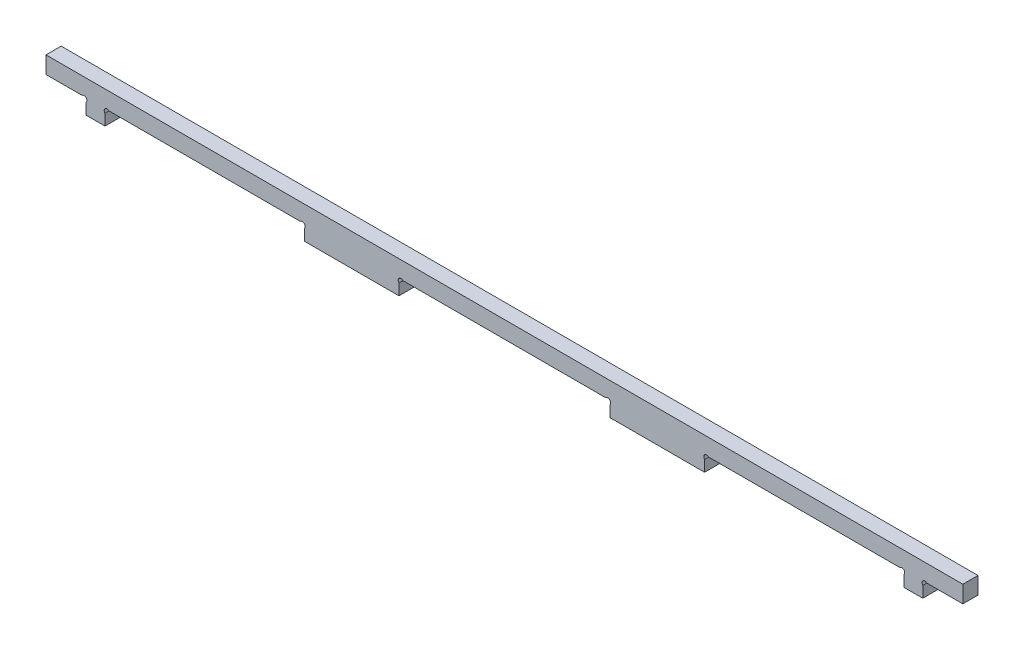
SolidWorks part; units mm, degrees
ref_plane "Plan de face" through (0, 0, 0) normal (0, 0, 1) x (1, 0, 0)
ref_plane "Plan de dessus" through (0, 0, 0) normal (0, 1, 0) x (1, 0, 0)
ref_plane "Plan de droite" through (0, 0, 0) normal (1, 0, 0) x (0, 0, -1)
sketch "Esquisse1" plane through (0, 0, 0) normal (0, 0, 1) x (1, 0, 0)
  line L136 (65.7875, 76.5822) -> (111.5449, 76.5822)
  line L137 (113.6662, 74.4609) -> (113.6662, 70.7035)
  line L138 (111.5449, 68.5822) -> (65.7875, 68.5822)
  line L139 (63.6662, 70.7035) -> (63.6662, 74.4609)
  line L140 (-47.6662, 70.7035) -> (-47.6662, 74.4609)
  line L141 (-95.5449, 68.5822) -> (-49.7875, 68.5822)
  line L142 (-97.6662, 74.4609) -> (-97.6662, 70.7035)
  line L143 (-49.7875, 76.5822) -> (-95.5449, 76.5822)
  line L144 (-212.8507, 74.4609) -> (-212.8507, 70.7035)
  line L145 (220.9721, 76.5822) -> (226.7294, 76.5822)
  line L146 (218.8507, 74.4609) -> (218.8507, 70.7035)
  line L147 (220.9721, 68.5822) -> (226.7294, 68.5822)
  line L148 (228.8507, 74.4609) -> (228.8507, 70.7035)
  line L149 (-204.9721, 68.5822) -> (-210.7294, 68.5822)
  line L150 (-202.8507, 74.4609) -> (-202.8507, 70.7035)
  line L151 (-204.9721, 76.5822) -> (-210.7294, 76.5822)
  arc A71 (63.6662, 70.7035) -> (65.7875, 68.5822) centre (64.7269, 69.6429) ccw
  arc A72 (65.7875, 76.5822) -> (63.6662, 74.4609) centre (64.7269, 75.5216) ccw
  arc A73 (113.6662, 74.4609) -> (111.5449, 76.5822) centre (112.6055, 75.5216) ccw
  arc A74 (111.5449, 68.5822) -> (113.6662, 70.7035) centre (112.6055, 69.6429) ccw
  arc A75 (-95.5449, 68.5822) -> (-97.6662, 70.7035) centre (-96.6055, 69.6429) cw
  arc A76 (-97.6662, 74.4609) -> (-95.5449, 76.5822) centre (-96.6055, 75.5216) cw
  arc A77 (-49.7875, 76.5822) -> (-47.6662, 74.4609) centre (-48.7269, 75.5216) cw
  arc A78 (-47.6662, 70.7035) -> (-49.7875, 68.5822) centre (-48.7269, 69.6429) cw
  arc A79 (220.9721, 76.5822) -> (218.8507, 74.4609) centre (219.9114, 75.5216) ccw
  arc A80 (228.8507, 74.4609) -> (226.7294, 76.5822) centre (227.7901, 75.5216) ccw
  arc A81 (226.7294, 68.5822) -> (228.8507, 70.7035) centre (227.7901, 69.6429) ccw
  arc A82 (218.8507, 70.7035) -> (220.9721, 68.5822) centre (219.9114, 69.6429) ccw
  arc A83 (-202.8507, 70.7035) -> (-204.9721, 68.5822) centre (-203.9114, 69.6429) cw
  arc A84 (-210.7294, 68.5822) -> (-212.8507, 70.7035) centre (-211.7901, 69.6429) cw
  arc A85 (-212.8507, 74.4609) -> (-210.7294, 76.5822) centre (-211.7901, 75.5216) cw
  arc A86 (-204.9721, 76.5822) -> (-202.8507, 74.4609) centre (-203.9114, 75.5216) cw
sketch "Esquisse2" plane through (0, 0, 0) normal (0, 0, 1) x (1, 0, 0)
  line L0 (-95.5449, 68.5822) -> (-49.7875, 68.5822) construction
  line L1 (-234, 77.5822) -> (250, 77.5822)
  line L2 (-234, 77.5822) -> (-234, 68.5822)
  line L3 (-234, 68.5822) -> (-214.9721, 68.5822)
  line L4 (250, 77.5822) -> (250, 68.5822)
  line L6 (-212.8507, 72.5822) -> (228.8507, 72.5822) construction
  line L7 (-212.8507, 74.4609) -> (-212.8507, 70.7035) construction
  line L8 (228.8507, 74.4609) -> (228.8507, 70.7035) construction
  line L9 (8, 72.5822) -> (8, 121.922) construction
  line L10 (8, 72.5822) -> (8, 68.5822) construction
  line L11 (-212.8507, 66.4609) -> (-212.8507, 60.5822)
  line L12 (-212.8507, 60.5822) -> (-202.8507, 60.5822)
  line L13 (-202.8507, 60.5822) -> (-202.8507, 66.4609)
  line L14 (-200.7294, 68.5822) -> (-99.7875, 68.5822)
  line L15 (-212.8507, 72.5822) -> (-212.8507, 68.5822) construction
  line L16 (-202.8507, 72.5822) -> (-202.8507, 68.5822) construction
  line L17 (-97.6662, 72.5822) -> (-97.6662, 68.5822) construction
  line L18 (-97.6662, 74.4609) -> (-97.6662, 70.7035) construction
  line L19 (-47.6662, 72.5822) -> (-47.6662, 68.5822) construction
  line L20 (-47.6662, 70.7035) -> (-47.6662, 74.4609) construction
  line L21 (63.6662, 72.5822) -> (63.6662, 68.5822) construction
  line L22 (63.6662, 70.7035) -> (63.6662, 74.4609) construction
  line L23 (113.6662, 72.5822) -> (113.6662, 68.5822) construction
  line L24 (113.6662, 74.4609) -> (113.6662, 70.7035) construction
  line L25 (228.8507, 72.5822) -> (228.8507, 68.5822) construction
  line L26 (218.8507, 72.5822) -> (218.8507, 68.5822) construction
  line L27 (218.8507, 74.4609) -> (218.8507, 70.7035) construction
  line L28 (228.8507, 66.4609) -> (228.8507, 60.5822)
  line L29 (228.8507, 60.5822) -> (218.8507, 60.5822)
  line L30 (218.8507, 60.5822) -> (218.8507, 66.4609)
  line L31 (113.6662, 66.4609) -> (113.6662, 60.5822)
  line L32 (113.6662, 60.5822) -> (63.6662, 60.5822)
  line L33 (63.6662, 60.5822) -> (63.6662, 66.4609)
  line L34 (-97.6662, 66.4609) -> (-97.6662, 60.5822)
  line L35 (-97.6662, 60.5822) -> (-47.6662, 60.5822)
  line L36 (-47.6662, 60.5822) -> (-47.6662, 66.4609)
  line L37 (-45.5449, 68.5822) -> (61.5449, 68.5822)
  line L38 (115.7875, 68.5822) -> (216.7294, 68.5822)
  line L39 (230.9721, 68.5822) -> (250, 68.5822)
  arc A0 (-212.8507, 70.7035) -> (-210.7294, 68.5822) centre (-211.7901, 69.6429) ccw construction
  arc A1 (-204.9721, 68.5822) -> (-202.8507, 70.7035) centre (-203.9114, 69.6429) ccw construction
  arc A2 (-97.6662, 70.7035) -> (-95.5449, 68.5822) centre (-96.6055, 69.6429) ccw construction
  arc A3 (-49.7875, 68.5822) -> (-47.6662, 70.7035) centre (-48.7269, 69.6429) ccw construction
  arc A4 (111.5449, 68.5822) -> (113.6662, 70.7035) centre (112.6055, 69.6429) ccw construction
  arc A5 (226.7294, 68.5822) -> (228.8507, 70.7035) centre (227.7901, 69.6429) ccw construction
  arc A6 (218.8507, 70.7035) -> (220.9721, 68.5822) centre (219.9114, 69.6429) ccw construction
  arc A7 (-212.8507, 66.4609) -> (-214.9721, 68.5822) centre (-213.9114, 67.5216) ccw
  arc A8 (-200.7294, 68.5822) -> (-202.8507, 66.4609) centre (-201.7901, 67.5216) ccw
  arc A9 (-97.6662, 66.4609) -> (-99.7875, 68.5822) centre (-98.7269, 67.5216) ccw
  arc A10 (-45.5449, 68.5822) -> (-47.6662, 66.4609) centre (-46.6055, 67.5216) ccw
  arc A11 (61.5449, 68.5822) -> (63.6662, 66.4609) centre (62.6055, 67.5216) cw
  arc A12 (113.6662, 66.4609) -> (115.7875, 68.5822) centre (114.7269, 67.5216) cw
  arc A13 (216.7294, 68.5822) -> (218.8507, 66.4609) centre (217.7901, 67.5216) cw
  arc A14 (228.8507, 66.4609) -> (230.9721, 68.5822) centre (229.9114, 67.5216) cw
extrude "Boss.-Extru.1" add sketch "Esquisse2" along normal blind 8
